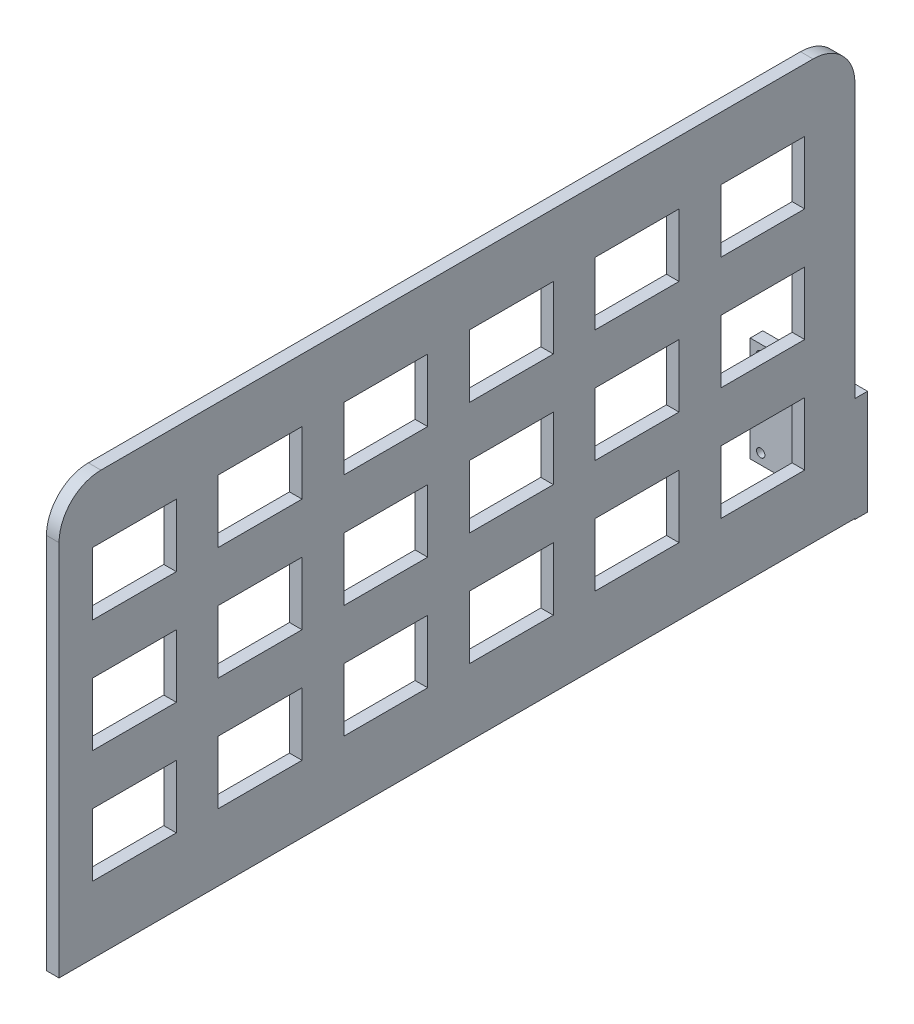
SolidWorks part; units mm, degrees
ref_plane "前视基准面" through (0, 0, 0) normal (0, 0, 1) x (1, 0, 0)
ref_plane "上视基准面" through (0, 0, 0) normal (0, 1, 0) x (1, 0, 0)
ref_plane "右视基准面" through (0, 0, 0) normal (1, 0, 0) x (0, 0, -1)
other "Configuration Table"
sketch "草图1" plane through (0, 0, 0) normal (0, 0, 1) x (1, 0, 0)
  line L0 (-112.6412, -73.6485) -> (-112.6412, -48.6485)
  line L1 (-112.6412, -73.6485) -> (-87.6412, -73.6485)
  line L2 (-112.6412, -48.6485) -> (-87.6412, -48.6485)
  line L3 (-87.6412, -73.6485) -> (-87.6412, -48.6485)
extrude "凸台-拉伸1" add sketch "草图1" along normal blind 3
sketch "草图2" plane through (0, 0, 3) normal (0, 0, 1) x (1, 0, 0)
  line L0 (-87.6412, -73.4528) -> (-87.6412, 26.5472)
  line L1 (-87.6412, -73.4528) -> (-90.6412, -73.4528)
  line L2 (-87.6412, 26.5472) -> (-90.6412, 26.5472)
  line L3 (-90.6412, -73.4528) -> (-90.6412, 26.5472)
  line L5 (-87.6412, -73.6485) -> (-87.6412, -48.6485) construction
  dimension "D1" = 100
  dimension "D2" = 3
extrude "凸台-拉伸2" add sketch "草图2" along normal blind 190
fillet "圆角1" radius 10 1 edges at (-90.6412, -61.0507, 3)
sketch "草图3" plane through (-87.6412, 0, 0) normal (1, 0, 0) x (0, 0, -1)
  line L83 (-35, 11.5472) -> (-15, 11.5472)
  line L84 (-35, 11.5472) -> (-35, -3.4528)
  line L85 (-35, -3.4528) -> (-15, -3.4528)
  line L86 (-15, 11.5472) -> (-15, -3.4528)
  line L152 (-65, 11.5472) -> (-65, -3.4528)
  line L153 (-65, 11.5472) -> (-45, 11.5472)
  line L154 (-45, 11.5472) -> (-45, -3.4528)
  line L155 (-65, -3.4528) -> (-45, -3.4528)
  line L156 (-95, 11.5472) -> (-95, -3.4528)
  line L157 (-95, 11.5472) -> (-75, 11.5472)
  line L158 (-75, 11.5472) -> (-75, -3.4528)
  line L159 (-95, -3.4528) -> (-75, -3.4528)
  line L160 (-125, 11.5472) -> (-125, -3.4528)
  line L161 (-125, 11.5472) -> (-105, 11.5472)
  line L162 (-105, 11.5472) -> (-105, -3.4528)
  line L163 (-125, -3.4528) -> (-105, -3.4528)
  line L164 (-155, 11.5472) -> (-155, -3.4528)
  line L165 (-155, 11.5472) -> (-135, 11.5472)
  line L166 (-135, 11.5472) -> (-135, -3.4528)
  line L167 (-155, -3.4528) -> (-135, -3.4528)
  line L168 (-185, 11.5472) -> (-185, -3.4528)
  line L169 (-185, 11.5472) -> (-165, 11.5472)
  line L170 (-165, 11.5472) -> (-165, -3.4528)
  line L171 (-185, -3.4528) -> (-165, -3.4528)
  line L172 (-65, -15.4528) -> (-65, -30.4528)
  line L173 (-65, -15.4528) -> (-45, -15.4528)
  line L174 (-45, -15.4528) -> (-45, -30.4528)
  line L175 (-65, -30.4528) -> (-45, -30.4528)
  line L176 (-95, -15.4528) -> (-95, -30.4528)
  line L177 (-95, -15.4528) -> (-75, -15.4528)
  line L178 (-75, -15.4528) -> (-75, -30.4528)
  line L179 (-95, -30.4528) -> (-75, -30.4528)
  line L180 (-125, -15.4528) -> (-125, -30.4528)
  line L181 (-125, -15.4528) -> (-105, -15.4528)
  line L182 (-105, -15.4528) -> (-105, -30.4528)
  line L183 (-125, -30.4528) -> (-105, -30.4528)
  line L184 (-155, -15.4528) -> (-155, -30.4528)
  line L185 (-155, -15.4528) -> (-135, -15.4528)
  line L186 (-135, -15.4528) -> (-135, -30.4528)
  line L187 (-155, -30.4528) -> (-135, -30.4528)
  line L188 (-185, -15.4528) -> (-185, -30.4528)
  line L189 (-185, -15.4528) -> (-165, -15.4528)
  line L190 (-165, -15.4528) -> (-165, -30.4528)
  line L191 (-185, -30.4528) -> (-165, -30.4528)
  line L192 (-65, -42.4528) -> (-65, -57.4528)
  line L193 (-65, -42.4528) -> (-45, -42.4528)
  line L194 (-45, -42.4528) -> (-45, -57.4528)
  line L195 (-65, -57.4528) -> (-45, -57.4528)
  line L196 (-95, -42.4528) -> (-95, -57.4528)
  line L197 (-95, -42.4528) -> (-75, -42.4528)
  line L198 (-75, -42.4528) -> (-75, -57.4528)
  line L199 (-95, -57.4528) -> (-75, -57.4528)
  line L200 (-125, -42.4528) -> (-125, -57.4528)
  line L201 (-125, -42.4528) -> (-105, -42.4528)
  line L202 (-105, -42.4528) -> (-105, -57.4528)
  line L203 (-125, -57.4528) -> (-105, -57.4528)
  line L204 (-155, -42.4528) -> (-155, -57.4528)
  line L205 (-155, -42.4528) -> (-135, -42.4528)
  line L206 (-135, -42.4528) -> (-135, -57.4528)
  line L207 (-155, -57.4528) -> (-135, -57.4528)
  line L208 (-185, -42.4528) -> (-185, -57.4528)
  line L209 (-185, -42.4528) -> (-165, -42.4528)
  line L210 (-165, -42.4528) -> (-165, -57.4528)
  line L211 (-185, -57.4528) -> (-165, -57.4528)
  line L212 (-35, -15.4528) -> (-35, -30.4528)
  line L213 (-35, -15.4528) -> (-15, -15.4528)
  line L214 (-15, -15.4528) -> (-15, -30.4528)
  line L215 (-35, -30.4528) -> (-15, -30.4528)
  line L216 (-35, -42.4528) -> (-35, -57.4528)
  line L217 (-35, -42.4528) -> (-15, -42.4528)
  line L218 (-15, -42.4528) -> (-15, -57.4528)
  line L219 (-35, -57.4528) -> (-15, -57.4528)
  line L220 (-193, 26.5472) -> (-3, 26.5472) construction
  line L221 (-3, -48.6485) -> (-3, 26.5472) construction
  dimension "D1" = 20
  dimension "D3" = 6
  dimension "D4" = 3
  dimension "D5" = 15
  dimension "D2" = 15
  dimension "D6" = 12
extrude "切除-拉伸2" cut sketch "草图3" against normal blind 10
fillet "圆角2" radius 10 1 edges at (-89.1412, 26.5472, 193)
fillet "圆角3" radius 10 1 edges at (-89.1412, 26.5472, 3)
sketch "草图4" plane through (0, 0, 3) normal (0, 0, 1) x (1, 0, 0)
  line L0 (-99.1162, -51.1485) -> (-101.1662, -51.1485) construction
  circle A0 centre (-110.1412, -51.1485) radius 1.05
  circle A1 centre (-110.1412, -61.1485) radius 1
  circle A2 centre (-110.1412, -71.1485) radius 1
  circle A5 centre (-100.1412, -71.1485) radius 1
  circle A8 centre (-100.1412, -68.6485) radius 1
  circle A9 centre (-100.1412, -51.1485) radius 1
  circle A10 centre (-100.1412, -53.6485) radius 1
extrude "切除-拉伸3" cut sketch "草图4" against normal blind 5 and the other way blind 5
